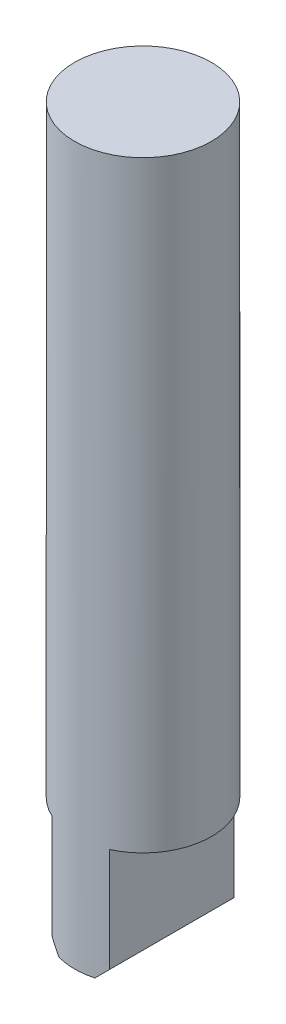
SolidWorks part; units mm, degrees
ref_plane "Front Plane" through (0, 0, 0) normal (0, 0, 1) x (1, 0, 0)
ref_plane "Top Plane" through (0, 0, 0) normal (0, 1, 0) x (1, 0, 0)
ref_plane "Right Plane" through (0, 0, 0) normal (1, 0, 0) x (0, 0, -1)
sketch "Sketch1" plane through (0, 0, 0) normal (0, 1, 0) x (1, 0, 0)
  circle A0 centre (0, 0) radius 4.775
  dimension "D1" = 9.55
extrude "Boss-Extrude1" add sketch "Sketch1" along normal blind 50
sketch "Sketch2" plane through (0, 50, 0) normal (0, 1, 0) x (1, 0, 0)
  line L1 (-2, 5.3245) -> (2, 5.3245)
  line L2 (-2, 5.3245) -> (-2, -5.3245)
  line L3 (-2, -5.3245) -> (2, -5.3245)
  line L4 (2, 5.3245) -> (2, -5.3245)
  line L5 (-2, 5.3245) -> (2, -5.3245) construction
  line L6 (-2, -5.3245) -> (2, 5.3245) construction
  circle A0 centre (0, 0) radius 5.6877
  point P0 (0, 0)
  dimension "D1" = 4
  dimension "D2" = 10.6489
sketch "Sketch3" plane through (0, 0, 0) normal (0, -1, 0) x (1, 0, 0)
  line L1 (-2, 5.4387) -> (2, 5.4387)
  line L2 (-2, 5.4387) -> (-2, -5.4387)
  line L3 (-2, -5.4387) -> (2, -5.4387)
  line L4 (2, 5.4387) -> (2, -5.4387)
  line L5 (-2, 5.4387) -> (2, -5.4387) construction
  line L6 (-2, -5.4387) -> (2, 5.4387) construction
  circle A0 centre (0, 0) radius 5.7948
  point P0 (0, 0)
  circle M6 centre (0, 0) radius 4.775
  dimension "D1" = 4
  dimension "D2" = 10.8774
extrude "Cut-Extrude2" cut sketch "Sketch3" against normal blind 8 contours L4 A0 M6 | L4 M6 | L2 M6 | L2 A0 M6
chamfer "Chamfer2" distance 0.75 angle 45 2 edges at (-2, 0, 0) (2, 0, 0)
